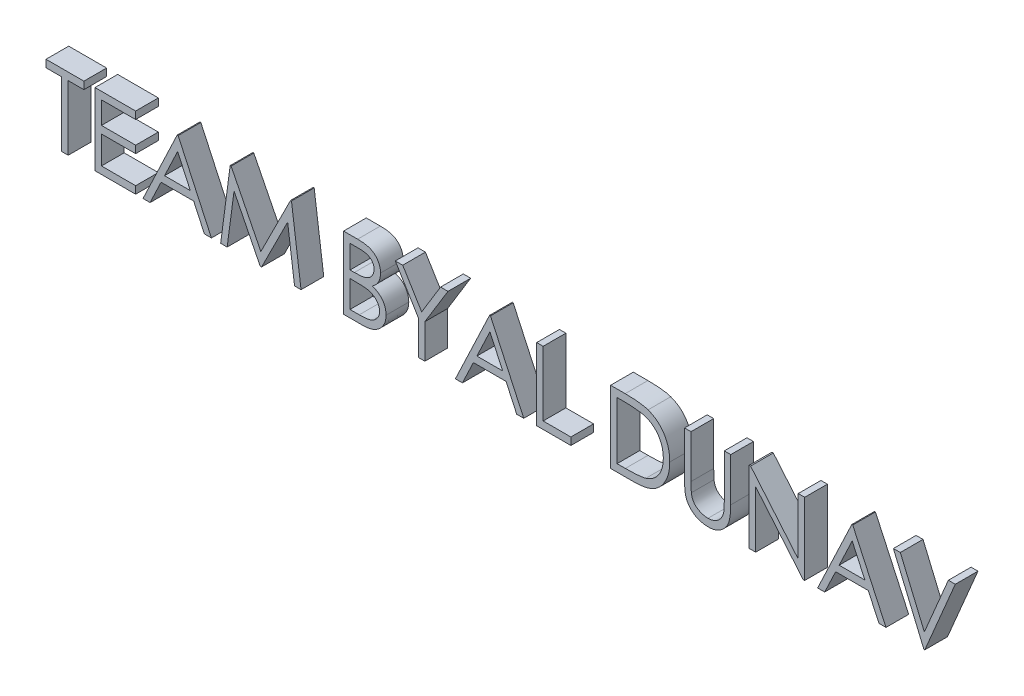
SolidWorks part; units mm, degrees
ref_plane "Front Plane" through (0, 0, 0) normal (0, 0, 1) x (1, 0, 0)
ref_plane "Top Plane" through (0, 0, 0) normal (0, 1, 0) x (1, 0, 0)
ref_plane "Right Plane" through (0, 0, 0) normal (1, 0, 0) x (0, 0, -1)
sketch "Sketch5" plane through (0, 0, 0) normal (0, 0, 1) x (1, 0, 0)
  line L1 (100, -5.62) -> (-100, -5.62) construction
  line L2 (100, -5.62) -> (100, 5.62) construction
  line L3 (100, 5.62) -> (-100, 5.62) construction
  line L4 (-100, -5.62) -> (-100, 5.62) construction
  line L5 (100, -5.62) -> (-100, 5.62) construction
  line L6 (100, 5.62) -> (-100, -5.62) construction
  text T0 "TEAM BYAL DUNAV" font "Century Gothic" height in points 36
  point P0 (0, 0)
  dimension "D1" = 200
  dimension "D2" = 11.24
extrude "Boss-Extrude3" add sketch "Sketch5" along normal blind 3
